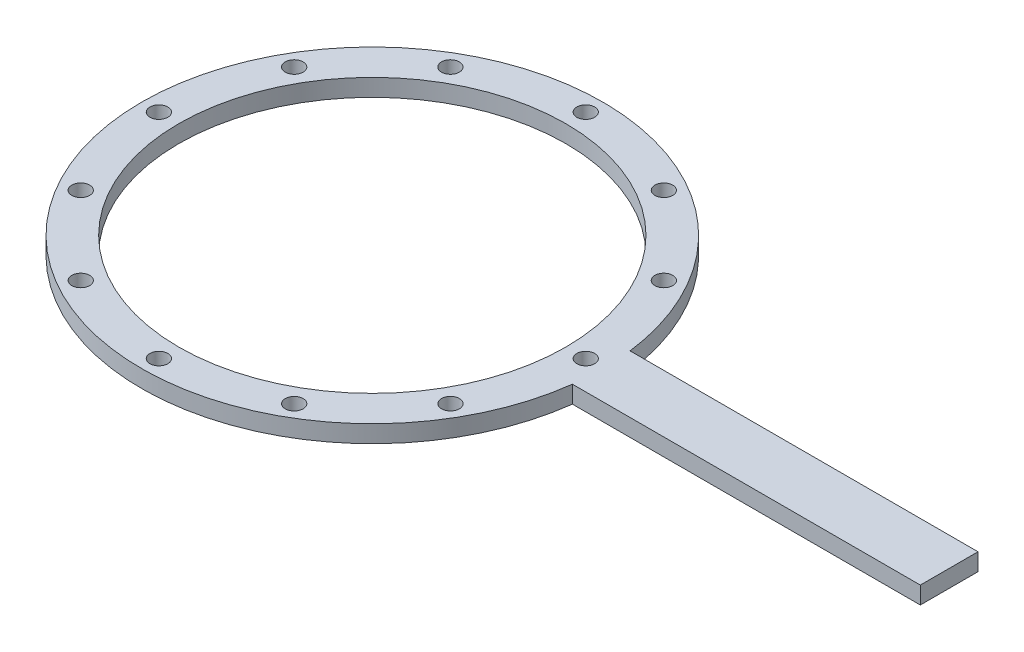
SolidWorks part; units mm, degrees
ref_plane "Front Plane" through (0, 0, 0) normal (0, 0, 1) x (1, 0, 0)
ref_plane "Top Plane" through (0, 0, 0) normal (0, 1, 0) x (1, 0, 0)
ref_plane "Right Plane" through (0, 0, 0) normal (1, 0, 0) x (0, 0, -1)
sketch "Sketch1" plane through (0, 0, 0) normal (0, 1, 0) x (1, 0, 0)
  line L1 (100, 5) -> (39.6863, 5)
  line L2 (100, 5) -> (100, -5)
  line L3 (100, -5) -> (39.6863, -5)
  line L4 (39.6863, 5) -> (39.6863, -5)
  line L5 (100, 5) -> (39.6863, -5) construction
  line L6 (100, -5) -> (39.6863, 5) construction
  circle A0 centre (0, 0) radius 40
  circle A1 centre (0, 0) radius 33.55
  point P3 (69.8431, 0)
  point P13 (100, 0)
  dimension "D1" = 100
  dimension "D2" = 80
  dimension "D3" = 67.1
  dimension "D4" = 10
extrude "Boss-Extrude1" add sketch "Sketch1" along normal blind 3 contours A0 L3 L2 L1 | L4 A0 A1
sketch "Sketch2" plane through (0, 3, 0) normal (0, 1, 0) x (1, 0, 0)
  circle A0 centre (37, 0) radius 1.55
  dimension "D1" = 3.1
  dimension "D2" = 37
extrude "Cut-Extrude1" cut sketch "Sketch2" against normal through all
pattern_circular "CirPattern1" count 12 over 360 about axis through (0, 0, 0) along (0, 1, 0) of "Cut-Extrude1"
